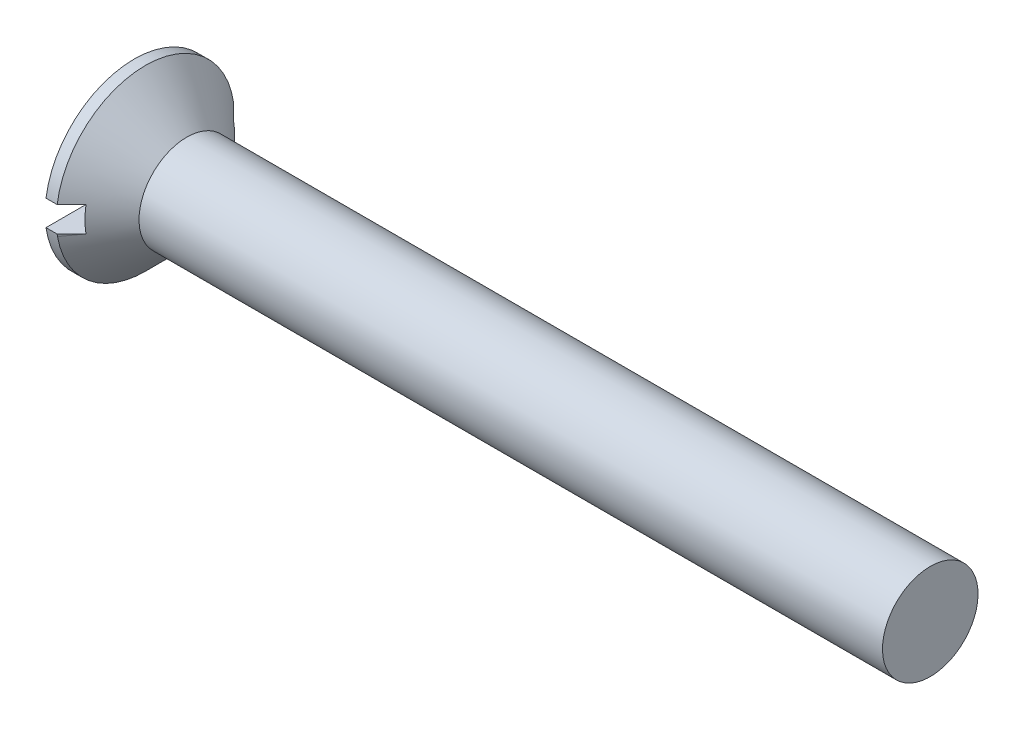
SolidWorks part; units mm, degrees
material "Plain Carbon Steel"
ref_plane "Front Plane" through (0, 0, 0) normal (0, 0, 1) x (1, 0, 0)
ref_plane "Top Plane" through (0, 0, 0) normal (0, 1, 0) x (1, 0, 0)
ref_plane "Right Plane" through (0, 0, 0) normal (1, 0, 0) x (0, 0, -1)
sketch "Sketch1" plane through (0, 0, 0) normal (0, 0, 1) x (1, 0, 0)
  line L0 (0, 0) -> (0, 2.8)
  line L1 (0, 2.8) -> (0.35, 2.8)
  line L2 (0.35, 2.8) -> (1.65, 1.5)
  line L3 (1.65, 1.5) -> (25, 1.5)
  line L4 (25, 1.5) -> (25, 0)
  line L5 (25, 0) -> (0, 0) construction
  line L6 (0, 0) -> (25, 0)
  dimension "D1" = 45
  dimension "D2" = 3
  dimension "D3" = 5.6
  dimension "D4" = 1.65
  dimension "D5" = 25
revolve "Revolve1" add sketch "Sketch1" angle 360 about L5
sketch "Sketch2" plane through (0, 0, 0) normal (-1, 0, 0) x (0, 0, 1)
  line L0 (2.8, 0) -> (-2.8, 0) construction
  line L1 (-2.8, 0.4) -> (2.8, 0.4)
  line L2 (-2.8, 0.4) -> (-2.8, -0.4)
  line L3 (-2.8, -0.4) -> (2.8, -0.4)
  line L4 (2.8, 0.4) -> (2.8, -0.4)
  circle A0 centre (0, 0) radius 2.8 construction
  dimension "D1" = 0.8
extrude "Cut-Extrude1" cut sketch "Sketch2" against normal blind 0.8
